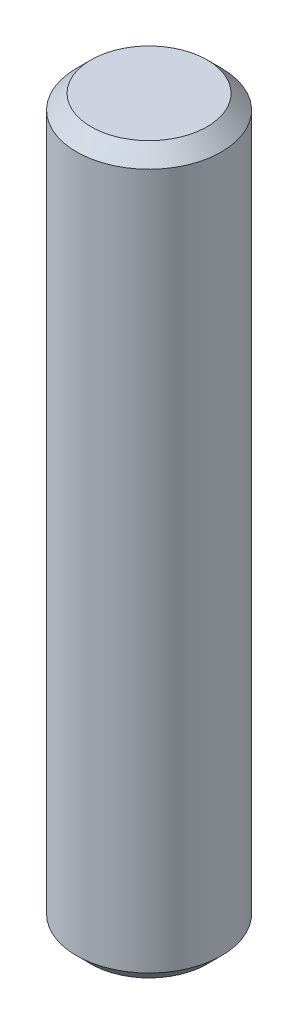
SolidWorks part; units mm, degrees
ref_plane "Face" through (0, 0, 0) normal (0, 0, 1) x (1, 0, 0)
ref_plane "Dessus" through (0, 0, 0) normal (0, 1, 0) x (1, 0, 0)
ref_plane "Droite" through (0, 0, 0) normal (1, 0, 0) x (0, 0, -1)
sketch "Esquisse1" plane through (0, 0, 0) normal (0, 0, 1) x (1, 0, 0)
  line L1 (2, -19.6) -> (2, -0.4)
  line L2 (0, 0) -> (0, -20.7306) construction
  line L3 (2, -19.6) -> (1.6, -20)
  line L4 (0, 0) -> (0, -20)
  line L5 (0, -20) -> (1.6, -20)
  line L6 (-2, 0) -> (2, 0) construction
  line L7 (0, 0) -> (1.6, 0)
  line L8 (2, -0.4) -> (1.6, 0)
  line L9 (0, 0) -> (0, 7.7458) construction
  dimension "D1" = 45
  dimension "D2" = 45
  dimension "Longueur" = 20
  dimension "Ch" = 0.4
  dimension "Rn" = 2
  dimension "Diamètre nominal" = 4
revolve "Base-Révolution" add sketch "Esquisse1" angle 360 about L9
equation "\"Rn@Esquisse1\" = \"Diamètre nominal@Esquisse1\"/2"
equation "\"Ch@Esquisse1\" = \"Diamètre nominal@Esquisse1\"*0.1"
